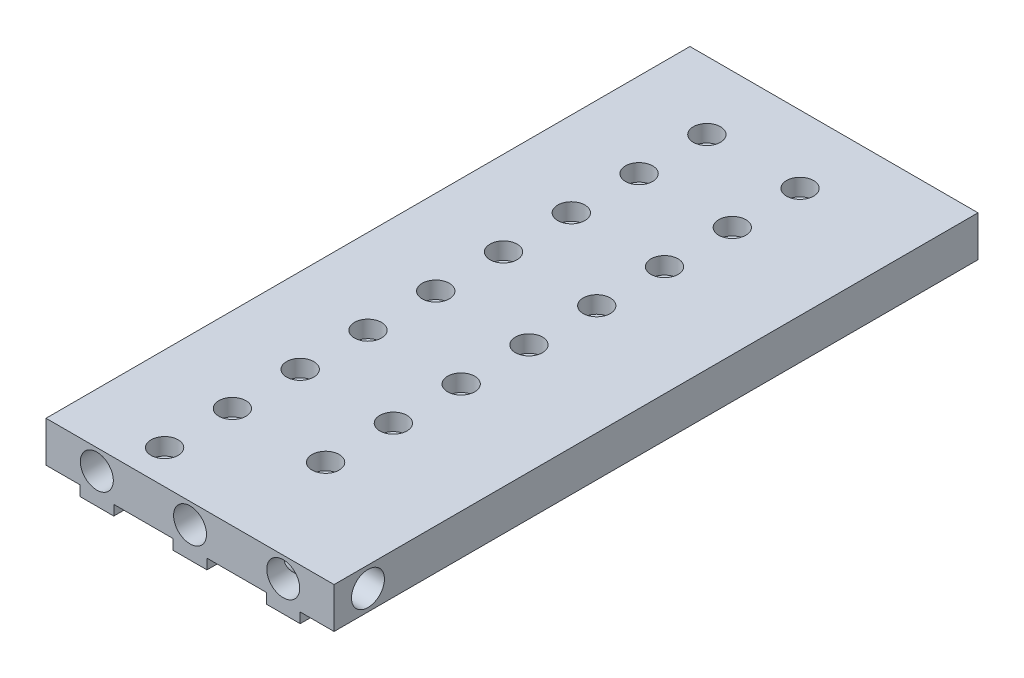
SolidWorks part; units mm, degrees
ref_plane "Front Plane" through (0, 0, 0) normal (0, 0, 1) x (1, 0, 0)
ref_plane "Top Plane" through (0, 0, 0) normal (0, 1, 0) x (1, 0, 0)
ref_plane "Right Plane" through (0, 0, 0) normal (1, 0, 0) x (0, 0, -1)
sketch "Sketch1" plane through (0, 0, 0) normal (0, 0, 1) x (1, 0, 0)
  line L0 (37.5, 0) -> (37.5, -3)
  line L1 (0, 0) -> (10, 0)
  line L2 (0, 0) -> (0, 12)
  line L3 (0, 12) -> (85, 12)
  line L4 (85, 0) -> (85, 12)
  line L6 (10, 0) -> (10, -3)
  line L7 (10, -3) -> (20, -3)
  line L8 (20, 0) -> (20, -3)
  line L10 (47.5, 0) -> (47.5, -3)
  line L11 (37.5, -3) -> (47.5, -3)
  line L12 (65, 0) -> (65, -3)
  line L14 (75, 0) -> (75, -3)
  line L15 (65, -3) -> (75, -3)
  line L16 (20, 0) -> (37.5, 0)
  line L17 (47.5, 0) -> (65, 0)
  line L18 (75, 0) -> (85, 0)
  circle A0 centre (15, 6) radius 4.864
  circle A1 centre (42.5, 6) radius 4.864
  circle A2 centre (70, 6) radius 4.864
  dimension "D7" = 6
  dimension "D9" = 9.728
  dimension "D1" = 12
  dimension "D2" = 85
  dimension "D3" = 3
  dimension "D4" = 10
  dimension "D5" = 10
  dimension "D8" = 15
  dimension "D6" = 3
  dimension "D10" = 3
extrude "Boss-Extrude1" add sketch "Sketch1" along normal blind 190
sketch "Sketch2" plane through (85, 0, 0) normal (1, 0, 0) x (0, 0, -1)
  line L0 (-190, 0) -> (-190, 12) construction
  line L1 (-190, 12) -> (0, 12) construction
  circle A0 centre (-180, 6) radius 4.864
  dimension "D1" = 9.728
  dimension "D3" = 6
  dimension "D2" = 10
extrude "Cut-Extrude1" cut sketch "Sketch2" against normal blind 40
sketch "Sketch5" plane through (0, 0, 0) normal (-1, 0, 0) x (0, 0, 1)
  line L0 (190, 12) -> (0, 12) construction
  line L1 (0, 12) -> (0, 0) construction
  circle A0 centre (10, 6) radius 4.864
  dimension "D1" = 9.728
  dimension "D2" = 6
  dimension "D3" = 10
extrude "Cut-Extrude3" cut sketch "Sketch5" against normal blind 40
sketch "Sketch6" plane through (0, 12, 0) normal (0, 1, 0) x (1, 0, 0)
  line L0 (0, -190) -> (0, 0) construction
  line L1 (85, -190) -> (0, -190) construction
  circle A0 centre (25, -180) radius 1.6
  circle A2 centre (52.5, -160) radius 1.6
  circle A3 centre (52.5, -140) radius 1.6
  circle A4 centre (52.5, -120) radius 1.6
  circle A5 centre (52.5, -100) radius 1.6
  circle A6 centre (52.5, -80) radius 1.6
  circle A7 centre (52.5, -60) radius 1.6
  circle A8 centre (52.5, -40) radius 1.6
  circle A9 centre (52.5, -20) radius 1.6
  circle A10 centre (25, -160) radius 1.6
  circle A11 centre (25, -140) radius 1.6
  circle A12 centre (25, -120) radius 1.6
  circle A13 centre (25, -100) radius 1.6
  circle A14 centre (25, -80) radius 1.6
  circle A15 centre (25, -60) radius 1.6
  circle A16 centre (25, -40) radius 1.6
  circle A17 centre (25, -20) radius 1.6
  circle A18 centre (52.5, -180) radius 1.6 [skipped]
  point P7 (0, 0)
  dimension "D1" = 3.2
  dimension "D2" = 25
  dimension "D3" = 10
  dimension "D4" = 2
  dimension "D5" = 9
extrude "Cut-Extrude4" cut sketch "Sketch6" against normal through all
sketch "Sketch7" plane through (0, 12, 0) normal (0, 1, 0) x (1, 0, 0)
  circle A0 centre (25, -180) radius 4
  circle A2 centre (52.5, -160) radius 4
  circle A3 centre (52.5, -140) radius 4
  circle A4 centre (52.5, -120) radius 4
  circle A5 centre (52.5, -100) radius 4
  circle A6 centre (52.5, -80) radius 4
  circle A7 centre (52.5, -60) radius 4
  circle A8 centre (52.5, -40) radius 4
  circle A9 centre (52.5, -20) radius 4
  circle A10 centre (25, -160) radius 4
  circle A11 centre (25, -140) radius 4
  circle A12 centre (25, -120) radius 4
  circle A13 centre (25, -100) radius 4
  circle A14 centre (25, -80) radius 4
  circle A15 centre (25, -60) radius 4
  circle A16 centre (25, -40) radius 4
  circle A17 centre (25, -20) radius 4
  circle A18 centre (52.5, -180) radius 4 [skipped]
  dimension "D1" = 8
  dimension "D2" = 2
  dimension "D3" = 9
extrude "Cut-Extrude5" cut sketch "Sketch7" against normal blind 5
